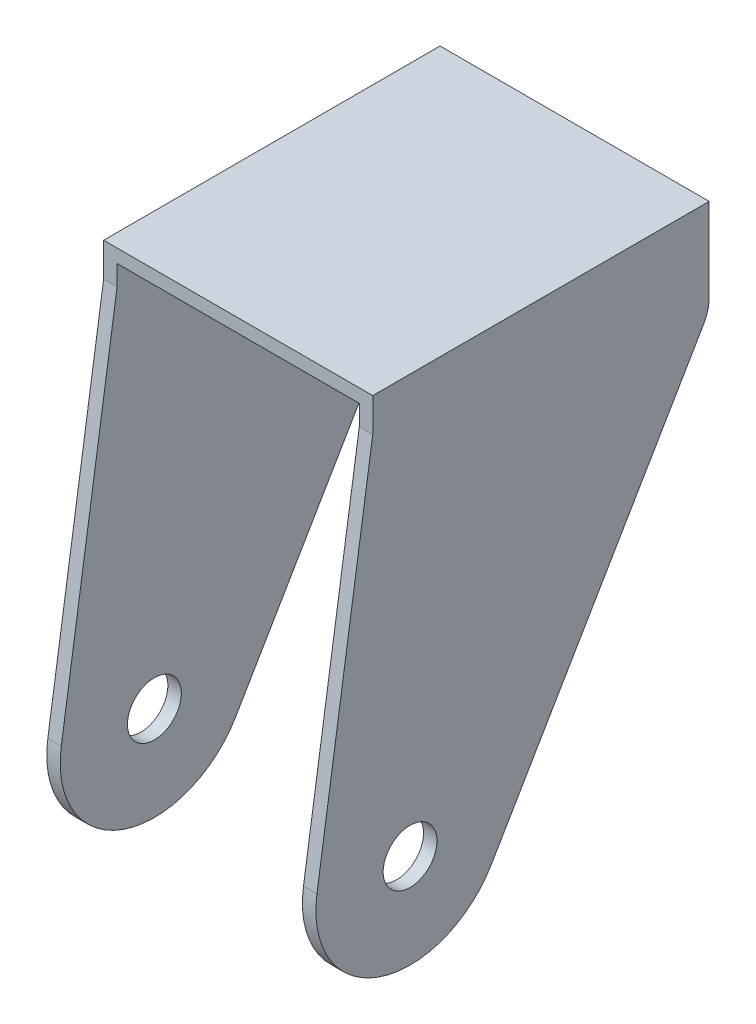
SolidWorks part; units mm, degrees
ref_plane "Front Plane" through (0, 0, 0) normal (0, 0, 1) x (1, 0, 0)
ref_plane "Top Plane" through (0, 0, 0) normal (0, 1, 0) x (1, 0, 0)
ref_plane "Right Plane" through (0, 0, 0) normal (1, 0, 0) x (0, 0, -1)
sketch "Sketch1" plane through (0, 0, 0) normal (1, 0, 0) x (0, 0, -1)
  line L0 (-13.8433, 2.0885) -> (-5.5457, 57.0885)
  line L1 (-5.5457, 57.0885) -> (-5.5457, 62.0885)
  line L2 (-5.5457, 62.0885) -> (44.4543, 62.0885)
  line L3 (44.4543, 62.0885) -> (44.4543, 49.7191)
  line L4 (43.629, 46.6822) -> (12.0743, -7.086)
  arc A0 (-13.8433, 2.0885) -> (12.0743, -7.086) centre (0, 0) ccw
  arc A1 (44.4543, 49.7191) -> (43.629, 46.6822) centre (38.4543, 49.7191) cw
  point P11 (44.4543, 48.0885)
  dimension "D1" = 28
  dimension "D6" = 6
  dimension "D2" = 60
  dimension "D3" = 5
  dimension "D4" = 50
  dimension "D5" = 14
extrude "Boss-Extrude1" add sketch "Sketch1" against normal blind 2
ref_plane "Plane1" through (-20, 0, 0) normal (1, 0, 0) x (0, 0, -1)
mirror "Mirror1" about plane through (-20, 0, 0) normal (1, 0, 0) of bodies 101
sketch "Sketch2" plane through (0, 62.0885, 0) normal (0, 1, 0) x (1, 0, 0)
  line L1 (-40, 44.4543) -> (0, 44.4543)
  line L2 (-40, 44.4543) -> (-40, -5.5457)
  line L3 (-40, -5.5457) -> (0, -5.5457)
  line L4 (0, 44.4543) -> (0, -5.5457)
extrude "Boss-Extrude2" add sketch "Sketch2" against normal blind 2
sketch "Sketch3" plane through (0, 62.0885, 0) normal (0, 1, 0) x (1, 0, 0)
  line L0 (0, 19.4543) -> (-40, 19.4543) construction
  line L1 (0, 44.4543) -> (0, -5.5457) construction
  line L2 (-40, 44.4543) -> (-40, -5.5457) construction
  line L3 (-40, 19.4543) -> (-20, -5.5457) construction
  line L4 (-40, -5.5457) -> (0, -5.5457) construction
  line L5 (-20, -5.5457) -> (-20, 44.4543) construction
  line L6 (-40, 44.4543) -> (0, 44.4543) construction
  line L10 (-18, 13.5942) -> (-9.6438, 29.4543)
  line L11 (-22, 13.5942) -> (-30.3562, 29.4543)
  arc A0 (-22, 13.5942) -> (-18, 13.5942) centre (-20, 23.3922) ccw
  arc A1 (-30.3562, 29.4543) -> (-9.6438, 29.4543) centre (-20, 23.3922) ccw
  arc A2 (-22.4, 11.6346) -> (-17.6, 11.6346) centre (-20, 23.3922) ccw construction
  dimension "D3" = 20
  dimension "D1" = 20.7123
  dimension "D2" = 2
  dimension "D4" = 15
  dimension "D5" = 2
extrude "Boss-Extrude3" add sketch "Sketch3" against normal blind 4
sketch "Sketch4" plane through (0, 60.0885, 0) normal (0, -1, 0) x (1, 0, 0)
  line L3 (-38, 5.5457) -> (-38, -44.4543)
  line L5 (-38, -44.4543) -> (-2, -44.4543)
  line L8 (-38, -44.4543) -> (-2, -44.4543)
  line L10 (-38, 5.5457) -> (-38, -44.4543)
  line L15 (-2, -44.4543) -> (-2, 5.5457)
  line L16 (-2, -44.4543) -> (-2, 5.5457)
  line L17 (-2, 5.5457) -> (-38, 5.5457)
  line L18 (-2, 5.5457) -> (-38, 5.5457)
  dimension "D1" = 0
sketch "Sketch5" plane through (0, 0, 0) normal (1, 0, 0) x (0, 0, -1)
  circle A0 centre (0, 0) radius 4
  dimension "D1" = 8
extrude "Cut-Extrude2" cut sketch "Sketch5" along a picked direction on the side against the normal blind 44 from surface at 0
sketch "Sketch6" plane through (0, 0, 0) normal (1, 0, 0) x (0, 0, -1)
  circle A2 centre (0, 0) radius 2.5
  dimension "D1" = 5
